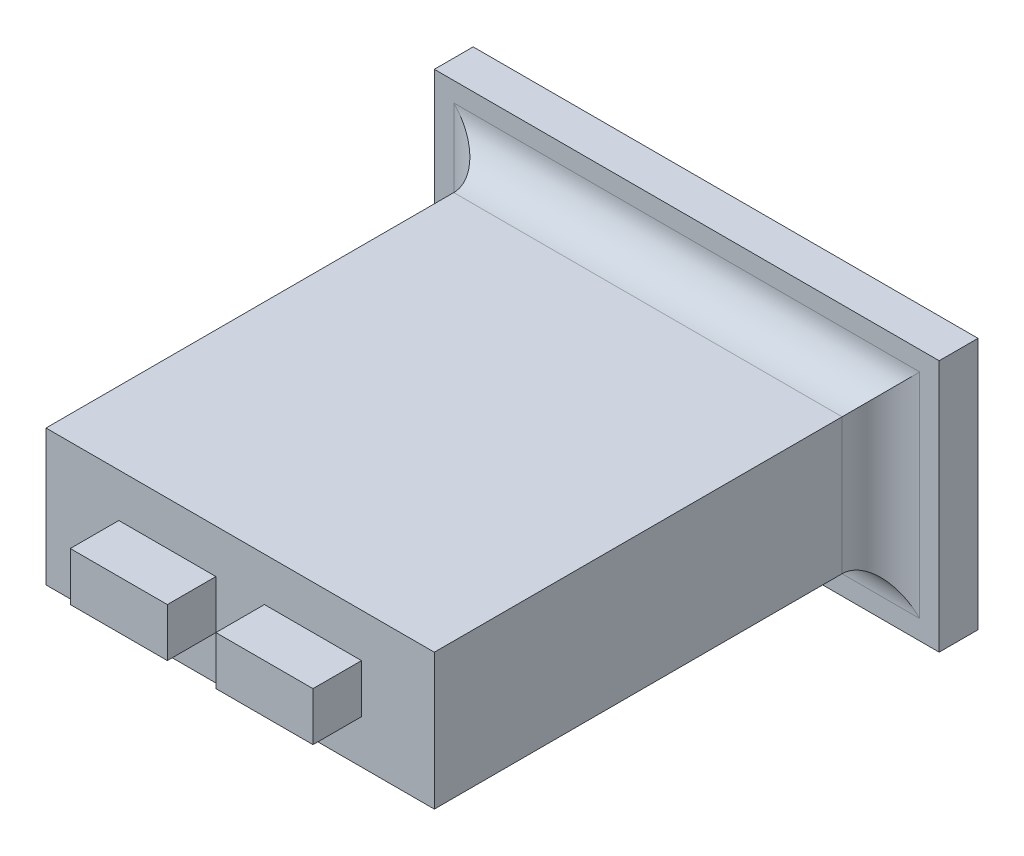
SolidWorks part; units mm, degrees
ref_plane "Plan de face" through (0, 0, 0) normal (0, 0, 1) x (1, 0, 0)
ref_plane "Plan de dessus" through (0, 0, 0) normal (0, 1, 0) x (1, 0, 0)
ref_plane "Plan de droite" through (0, 0, 0) normal (1, 0, 0) x (0, 0, -1)
sketch "Esquisse1" plane through (0, 0, 0) normal (0, 0, 1) x (1, 0, 0)
  line L1 (0, 0) -> (20, 0)
  line L2 (0, 0) -> (0, 7)
  line L3 (0, 7) -> (20, 7)
  line L4 (20, 0) -> (20, 7)
  dimension "D1" = 20
  dimension "D2" = 7
extrude "Boss.-Extru.1" add sketch "Esquisse1" along normal blind 23
sketch "Esquisse2" plane through (0, 0, 23) normal (0, 0, 1) x (1, 0, 0)
  line L0 (0, 7) -> (0, 0) construction
  line L1 (3.75, 4.75) -> (8.75, 4.75)
  line L2 (3.75, 4.75) -> (3.75, 2.25)
  line L3 (3.75, 2.25) -> (8.75, 2.25)
  line L4 (8.75, 4.75) -> (8.75, 2.25)
  line L5 (11.25, 4.75) -> (16.25, 4.75)
  line L6 (11.25, 4.75) -> (11.25, 2.25)
  line L7 (11.25, 2.25) -> (16.25, 2.25)
  line L8 (16.25, 4.75) -> (16.25, 2.25)
  line L9 (20, 0) -> (20, 7) construction
  line L10 (0, 0) -> (20, 0) construction
  line L11 (20, 7) -> (0, 7) construction
  dimension "D1" = 2.5
  dimension "D2" = 5
  dimension "D3" = 5
  dimension "D4" = 2.5
  dimension "D5" = 2.5
  dimension "D6" = 3.75
  dimension "D7" = 3.75
  dimension "D8" = 2.25
  dimension "D9" = 2.25
extrude "Boss.-Extru.2" add sketch "Esquisse2" along normal blind 2.5
sketch "Esquisse3" plane through (0, 0, 0) normal (0, 0, -1) x (-1, 0, 0)
  line L0 (0, 0) -> (-20, 0) construction
  line L1 (-20, 7) -> (-23, 7)
  line L2 (-20, 7) -> (-20, 10)
  line L3 (-20, 10) -> (-23, 10)
  line L4 (-23, 7) -> (-23, 10)
  line L5 (-23, 10) -> (3, 10)
  line L6 (-23, 10) -> (-23, -3)
  line L7 (-23, -3) -> (3, -3)
  line L8 (3, 10) -> (3, -3)
  line L9 (0, 7) -> (0, 0) construction
  line M9 (0, 0) -> (0, 7)
  line M10 (0, 7) -> (-20, 7)
  line M11 (-20, 7) -> (-20, 0)
  line M12 (-20, 0) -> (0, 0)
  dimension "D1" = 3
  dimension "D2" = 3
  dimension "D3" = 26
  dimension "D4" = 13
  dimension "D5" = 3
  dimension "D6" = 3
extrude "Boss.-Extru.3" add sketch "Esquisse3" along normal blind 2 contours L4 L1 L2 L3 | L8 L5 L2 L1 L6 L7 M10 M9 M12 M11 | M12 M9 M10 M11
fillet "Congé1" radius 2 4 edges at (10, 7, 0) (0, 3.5, 0) (20, 3.5, 0) (10, 0, 0)
